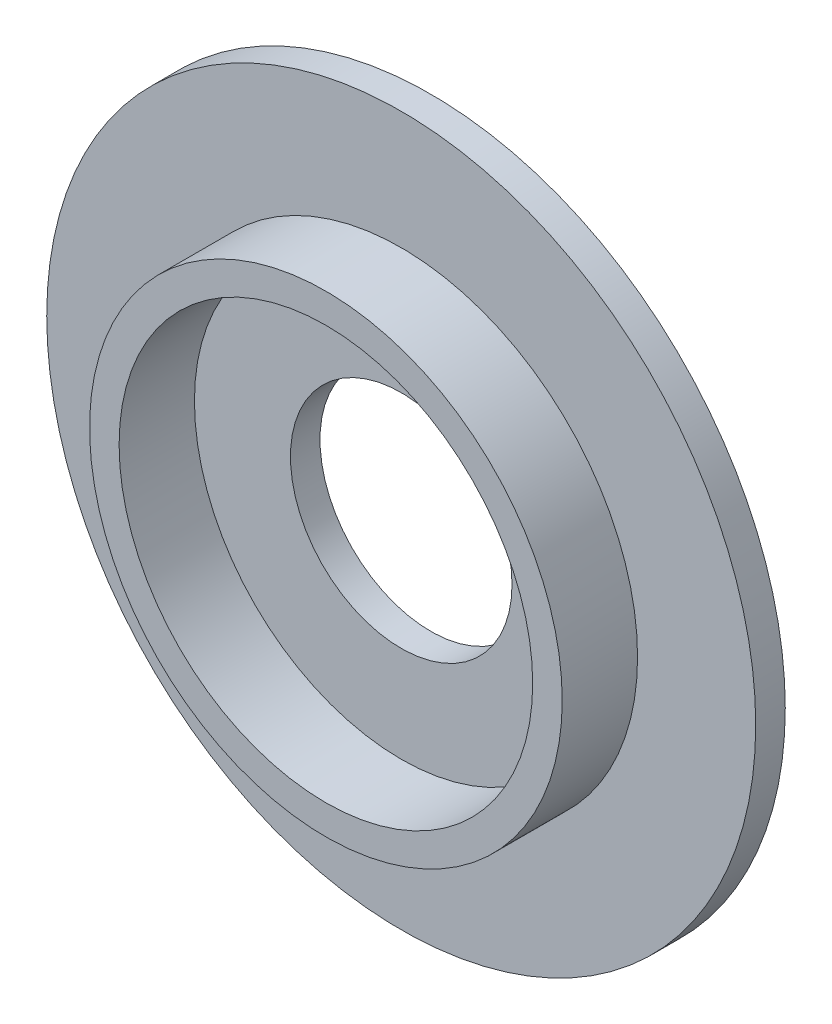
SolidWorks part; units mm, degrees
ref_plane "前视" through (0, 0, 0) normal (0, 0, 1) x (1, 0, 0)
ref_plane "上视" through (0, 0, 0) normal (0, 1, 0) x (1, 0, 0)
ref_plane "右视" through (0, 0, 0) normal (1, 0, 0) x (0, 0, -1)
sketch "草图1" plane through (0, 0, 0) normal (0, 0, 1) x (1, 0, 0)
  line L0 (0, 155.7418) -> (0, -151.0312) construction
  line L1 (155.2911, 0) -> (-154.426, 0) construction
  circle A0 centre (0, 0) radius 120
  circle A1 centre (0, 0) radius 37.5
  dimension "D1" = 75
  dimension "D2" = 240
extrude "拉伸1" add sketch "草图1" along normal blind 10
sketch "草图2" plane through (0, 0, 10) normal (0, 0, 1) x (1, 0, 0)
  circle A0 centre (0, 0) radius 80
  circle A1 centre (0, 0) radius 70
  dimension "D1" = 140
  dimension "D2" = 160
extrude "拉伸2" add sketch "草图2" along normal blind 25.5
